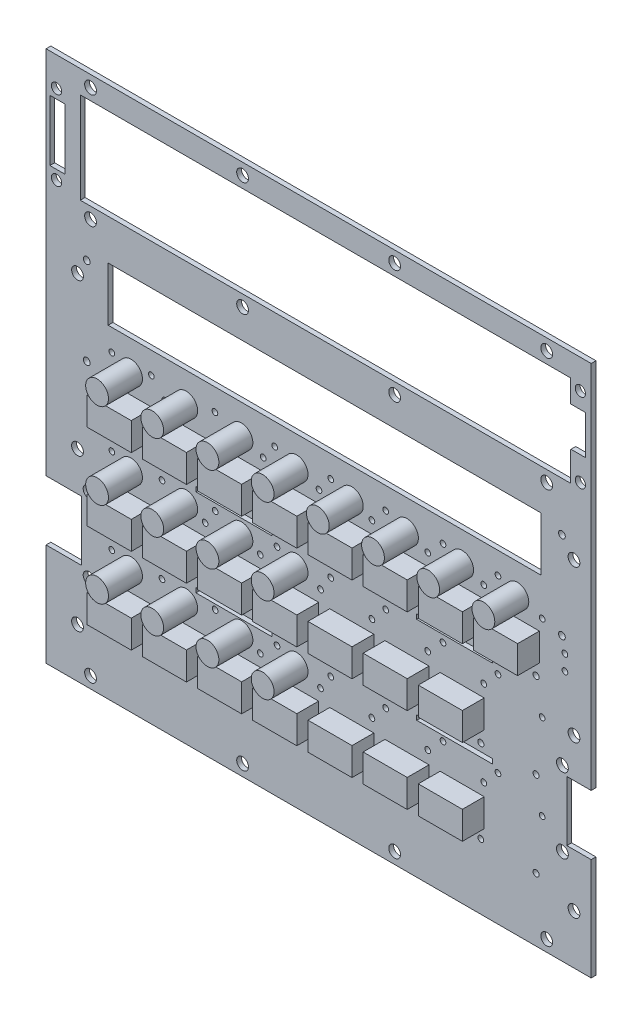
SolidWorks part; units mm, degrees
ref_plane "Front Plane" through (0, 0, 0) normal (0, 0, 1) x (1, 0, 0)
ref_plane "Top Plane" through (0, 0, 0) normal (0, 1, 0) x (1, 0, 0)
ref_plane "Right Plane" through (0, 0, 0) normal (1, 0, 0) x (0, 0, -1)
sketch "Sketch1" plane through (0, 0, 0) normal (0, 0, 1) x (1, 0, 0)
  line L0 (0, 0) -> (182.118, 0)
  line L1 (182.118, 0) -> (182.118, 34.2468)
  line L2 (182.118, 34.2468) -> (173.9875, 34.2468)
  line L3 (173.9875, 34.2468) -> (173.9875, 54.2468)
  line L4 (173.9875, 54.2468) -> (182.118, 54.2468)
  line L5 (182.118, 54.2468) -> (182.118, 177.8)
  line L6 (182.118, 177.8) -> (0, 177.8)
  line L7 (0, 177.8) -> (0, 54.2468)
  line L8 (0, 54.2468) -> (11.8694, 54.2468)
  line L9 (11.8694, 54.2468) -> (11.8694, 34.2468)
  line L10 (11.8694, 34.2468) -> (0, 34.2468)
  line L11 (0, 34.2468) -> (0, 0)
  line L12 (20.7391, 108.1786) -> (20.7391, 126.1796)
  line L13 (20.7391, 126.1796) -> (165.3007, 126.1796)
  line L14 (165.3007, 126.1796) -> (165.3007, 108.1786)
  line L15 (165.3007, 108.1786) -> (20.7391, 108.1786)
  line L16 (1.27, 144.653) -> (1.27, 164.973)
  line L17 (1.27, 164.973) -> (6.35, 164.973)
  line L18 (6.35, 164.973) -> (6.35, 144.653)
  line L19 (6.35, 144.653) -> (1.27, 144.653)
  line L20 (12.7, 170.18) -> (175.26, 170.18)
  line L21 (175.26, 170.18) -> (175.26, 162.6616)
  line L22 (175.26, 162.6616) -> (180.086, 162.6616)
  line L23 (180.086, 162.6616) -> (180.2892, 162.4584)
  line L24 (180.2892, 162.4584) -> (180.2892, 149.606)
  line L25 (180.2892, 149.606) -> (175.3616, 149.606)
  line L26 (175.3616, 149.606) -> (175.26, 149.5044)
  line L27 (175.26, 149.5044) -> (175.26, 139.7)
  line L28 (175.26, 139.7) -> (12.7, 139.7)
  line L29 (12.7, 139.7) -> (11.43, 139.7)
  line L30 (11.43, 139.7) -> (11.43, 170.18)
  line L31 (11.43, 170.18) -> (12.7, 170.18)
  line L32 (50.0634, 45.4152) -> (50.0634, 47.0027)
  line L33 (50.0634, 47.0027) -> (75.4634, 47.0027)
  line L34 (75.4634, 47.0027) -> (75.4634, 45.4152)
  line L35 (75.4634, 45.4152) -> (50.0634, 45.4152)
  line L36 (123.8134, 45.4152) -> (123.8134, 47.0027)
  line L37 (123.8134, 47.0027) -> (149.2134, 47.0027)
  line L38 (149.2134, 47.0027) -> (149.2134, 45.4152)
  line L39 (149.2134, 45.4152) -> (123.8134, 45.4152)
  line L40 (123.8134, 74.6252) -> (123.8134, 76.2127)
  line L41 (123.8134, 76.2127) -> (149.2134, 76.2127)
  line L42 (149.2134, 76.2127) -> (149.2134, 74.6252)
  line L43 (149.2134, 74.6252) -> (123.8134, 74.6252)
  line L44 (50.0634, 74.6252) -> (50.0634, 76.2127)
  line L45 (50.0634, 76.2127) -> (75.4634, 76.2127)
  line L46 (75.4634, 76.2127) -> (75.4634, 74.6252)
  line L47 (75.4634, 74.6252) -> (50.0634, 74.6252)
extrude "BOARD" add sketch "Sketch1" along normal blind 1.5921 separate body
ref_plane "Plane1" through (0, 0, 1.5921) normal (0, 0, 1) x (1, 0, 0)
sketch "Sketch11" plane through (0, 0, 1.5921) normal (0, 0, 1) x (1, 0, 0)
  circle A0 centre (83.7097, 41.1988) radius 3.81
extrude "LED-KINGBRIGHT_3P_2P54-10" add sketch "Sketch11" along normal blind 11.3538 separate body
sketch "Sketch12" plane through (0, 0, 1.5921) normal (0, 0, 1) x (1, 0, 0)
  circle A0 centre (65.2722, 41.1988) radius 3.81
extrude "LED-KINGBRIGHT_3P_2P54-11" add sketch "Sketch12" along normal blind 11.3538 separate body
sketch "Sketch13" plane through (0, 0, 1.5921) normal (0, 0, 1) x (1, 0, 0)
  circle A0 centre (46.8347, 41.1988) radius 3.81
extrude "LED-KINGBRIGHT_3P_2P54-12" add sketch "Sketch13" along normal blind 11.3538 separate body
sketch "Sketch14" plane through (0, 0, 1.5921) normal (0, 0, 1) x (1, 0, 0)
  circle A0 centre (28.3972, 41.1988) radius 3.81
extrude "LED-KINGBRIGHT_3P_2P54-13" add sketch "Sketch14" along normal blind 11.3538 separate body
sketch "Sketch15" plane through (0, 0, 1.5921) normal (0, 0, 1) x (1, 0, 0)
  circle A0 centre (83.7097, 69.7738) radius 3.81
extrude "LED-KINGBRIGHT_3P_2P54-14" add sketch "Sketch15" along normal blind 11.3538 separate body
sketch "Sketch16" plane through (0, 0, 1.5921) normal (0, 0, 1) x (1, 0, 0)
  circle A0 centre (65.2722, 69.7738) radius 3.81
extrude "LED-KINGBRIGHT_3P_2P54-15" add sketch "Sketch16" along normal blind 11.3538 separate body
sketch "Sketch17" plane through (0, 0, 1.5921) normal (0, 0, 1) x (1, 0, 0)
  circle A0 centre (46.8347, 69.7738) radius 3.81
extrude "LED-KINGBRIGHT_3P_2P54-16" add sketch "Sketch17" along normal blind 11.3538 separate body
sketch "Sketch18" plane through (0, 0, 1.5921) normal (0, 0, 1) x (1, 0, 0)
  circle A0 centre (28.3972, 69.7738) radius 3.81
extrude "LED-KINGBRIGHT_3P_2P54-17" add sketch "Sketch18" along normal blind 11.3538 separate body
sketch "Sketch19" plane through (0, 0, 1.5921) normal (0, 0, 1) x (1, 0, 0)
  circle A0 centre (157.4597, 98.3488) radius 3.81
extrude "LED-KINGBRIGHT_3P_2P54-18" add sketch "Sketch19" along normal blind 11.3538 separate body
sketch "Sketch20" plane through (0, 0, 1.5921) normal (0, 0, 1) x (1, 0, 0)
  circle A0 centre (139.0222, 98.3488) radius 3.81
extrude "LED-KINGBRIGHT_3P_2P54-19" add sketch "Sketch20" along normal blind 11.3538 separate body
sketch "Sketch21" plane through (0, 0, 1.5921) normal (0, 0, 1) x (1, 0, 0)
  circle A0 centre (120.5847, 98.3488) radius 3.81
extrude "LED-KINGBRIGHT_3P_2P54-20" add sketch "Sketch21" along normal blind 11.3538 separate body
sketch "Sketch22" plane through (0, 0, 1.5921) normal (0, 0, 1) x (1, 0, 0)
  circle A0 centre (102.1472, 98.3488) radius 3.81
extrude "LED-KINGBRIGHT_3P_2P54-21" add sketch "Sketch22" along normal blind 11.3538 separate body
sketch "Sketch23" plane through (0, 0, 1.5921) normal (0, 0, 1) x (1, 0, 0)
  circle A0 centre (83.7097, 98.3488) radius 3.81
extrude "LED-KINGBRIGHT_3P_2P54-22" add sketch "Sketch23" along normal blind 11.3538 separate body
sketch "Sketch24" plane through (0, 0, 1.5921) normal (0, 0, 1) x (1, 0, 0)
  circle A0 centre (65.2722, 98.3488) radius 3.81
extrude "LED-KINGBRIGHT_3P_2P54-23" add sketch "Sketch24" along normal blind 11.3538 separate body
sketch "Sketch25" plane through (0, 0, 1.5921) normal (0, 0, 1) x (1, 0, 0)
  circle A0 centre (46.8347, 98.3488) radius 3.81
extrude "LED-KINGBRIGHT_3P_2P54-24" add sketch "Sketch25" along normal blind 11.3538 separate body
sketch "Sketch26" plane through (0, 0, 1.5921) normal (0, 0, 1) x (1, 0, 0)
  circle A0 centre (28.3972, 98.3488) radius 3.81
extrude "LED-KINGBRIGHT_3P_2P54-25" add sketch "Sketch26" along normal blind 11.3538 separate body
sketch "Sketch29" plane through (0, 0, 1.5921) normal (0, 0, 1) x (1, 0, 0)
  line L0 (131.6562, 25.3238) -> (131.6562, 34.5948)
  line L1 (131.6562, 34.5948) -> (146.3882, 34.5948)
  line L2 (146.3882, 34.5948) -> (146.3882, 25.3238)
  line L3 (146.3882, 25.3238) -> (131.6562, 25.3238)
extrude "SWITCH-MCDTS2-3" add sketch "Sketch29" along normal blind 7.3 separate body
sketch "Sketch30" plane through (0, 0, 1.5921) normal (0, 0, 1) x (1, 0, 0)
  line L0 (113.2187, 25.3238) -> (113.2187, 34.5948)
  line L1 (113.2187, 34.5948) -> (127.9507, 34.5948)
  line L2 (127.9507, 34.5948) -> (127.9507, 25.3238)
  line L3 (127.9507, 25.3238) -> (113.2187, 25.3238)
extrude "SWITCH-MCDTS2-4" add sketch "Sketch30" along normal blind 7.3 separate body
sketch "Sketch31" plane through (0, 0, 1.5921) normal (0, 0, 1) x (1, 0, 0)
  line L0 (94.7812, 25.3238) -> (94.7812, 34.5948)
  line L1 (94.7812, 34.5948) -> (109.5132, 34.5948)
  line L2 (109.5132, 34.5948) -> (109.5132, 25.3238)
  line L3 (109.5132, 25.3238) -> (94.7812, 25.3238)
extrude "SWITCH-MCDTS2-5" add sketch "Sketch31" along normal blind 7.3 separate body
sketch "Sketch32" plane through (0, 0, 1.5921) normal (0, 0, 1) x (1, 0, 0)
  line L0 (76.3437, 25.3238) -> (76.3437, 34.5948)
  line L1 (76.3437, 34.5948) -> (91.0757, 34.5948)
  line L2 (91.0757, 34.5948) -> (91.0757, 25.3238)
  line L3 (91.0757, 25.3238) -> (76.3437, 25.3238)
extrude "SWITCH-MCDTS2-6" add sketch "Sketch32" along normal blind 7.3 separate body
sketch "Sketch33" plane through (0, 0, 1.5921) normal (0, 0, 1) x (1, 0, 0)
  line L0 (57.9062, 25.3238) -> (57.9062, 34.5948)
  line L1 (57.9062, 34.5948) -> (72.6382, 34.5948)
  line L2 (72.6382, 34.5948) -> (72.6382, 25.3238)
  line L3 (72.6382, 25.3238) -> (57.9062, 25.3238)
extrude "SWITCH-MCDTS2-7" add sketch "Sketch33" along normal blind 7.3 separate body
sketch "Sketch34" plane through (0, 0, 1.5921) normal (0, 0, 1) x (1, 0, 0)
  line L0 (39.4687, 25.3238) -> (39.4687, 34.5948)
  line L1 (39.4687, 34.5948) -> (54.2007, 34.5948)
  line L2 (54.2007, 34.5948) -> (54.2007, 25.3238)
  line L3 (54.2007, 25.3238) -> (39.4687, 25.3238)
extrude "SWITCH-MCDTS2-8" add sketch "Sketch34" along normal blind 7.3 separate body
sketch "Sketch35" plane through (0, 0, 1.5921) normal (0, 0, 1) x (1, 0, 0)
  line L0 (21.0312, 25.3238) -> (21.0312, 34.5948)
  line L1 (21.0312, 34.5948) -> (35.7632, 34.5948)
  line L2 (35.7632, 34.5948) -> (35.7632, 25.3238)
  line L3 (35.7632, 25.3238) -> (21.0312, 25.3238)
extrude "SWITCH-MCDTS2-9" add sketch "Sketch35" along normal blind 7.3 separate body
sketch "Sketch36" plane through (0, 0, 1.5921) normal (0, 0, 1) x (1, 0, 0)
  line L0 (131.6562, 53.8988) -> (131.6562, 63.1698)
  line L1 (131.6562, 63.1698) -> (146.3882, 63.1698)
  line L2 (146.3882, 63.1698) -> (146.3882, 53.8988)
  line L3 (146.3882, 53.8988) -> (131.6562, 53.8988)
extrude "SWITCH-MCDTS2-10" add sketch "Sketch36" along normal blind 7.3 separate body
sketch "Sketch37" plane through (0, 0, 1.5921) normal (0, 0, 1) x (1, 0, 0)
  line L0 (113.2187, 53.8988) -> (113.2187, 63.1698)
  line L1 (113.2187, 63.1698) -> (127.9507, 63.1698)
  line L2 (127.9507, 63.1698) -> (127.9507, 53.8988)
  line L3 (127.9507, 53.8988) -> (113.2187, 53.8988)
extrude "SWITCH-MCDTS2-11" add sketch "Sketch37" along normal blind 7.3 separate body
sketch "Sketch38" plane through (0, 0, 1.5921) normal (0, 0, 1) x (1, 0, 0)
  line L0 (94.7812, 53.8988) -> (94.7812, 63.1698)
  line L1 (94.7812, 63.1698) -> (109.5132, 63.1698)
  line L2 (109.5132, 63.1698) -> (109.5132, 53.8988)
  line L3 (109.5132, 53.8988) -> (94.7812, 53.8988)
extrude "SWITCH-MCDTS2-12" add sketch "Sketch38" along normal blind 7.3 separate body
sketch "Sketch39" plane through (0, 0, 1.5921) normal (0, 0, 1) x (1, 0, 0)
  line L0 (76.3437, 53.8988) -> (76.3437, 63.1698)
  line L1 (76.3437, 63.1698) -> (91.0757, 63.1698)
  line L2 (91.0757, 63.1698) -> (91.0757, 53.8988)
  line L3 (91.0757, 53.8988) -> (76.3437, 53.8988)
extrude "SWITCH-MCDTS2-13" add sketch "Sketch39" along normal blind 7.3 separate body
sketch "Sketch40" plane through (0, 0, 1.5921) normal (0, 0, 1) x (1, 0, 0)
  line L0 (57.9062, 53.8988) -> (57.9062, 63.1698)
  line L1 (57.9062, 63.1698) -> (72.6382, 63.1698)
  line L2 (72.6382, 63.1698) -> (72.6382, 53.8988)
  line L3 (72.6382, 53.8988) -> (57.9062, 53.8988)
extrude "SWITCH-MCDTS2-14" add sketch "Sketch40" along normal blind 7.3 separate body
sketch "Sketch41" plane through (0, 0, 1.5921) normal (0, 0, 1) x (1, 0, 0)
  line L0 (39.4687, 53.8988) -> (39.4687, 63.1698)
  line L1 (39.4687, 63.1698) -> (54.2007, 63.1698)
  line L2 (54.2007, 63.1698) -> (54.2007, 53.8988)
  line L3 (54.2007, 53.8988) -> (39.4687, 53.8988)
extrude "SWITCH-MCDTS2-15" add sketch "Sketch41" along normal blind 7.3 separate body
sketch "Sketch42" plane through (0, 0, 1.5921) normal (0, 0, 1) x (1, 0, 0)
  line L0 (21.0312, 53.8988) -> (21.0312, 63.1698)
  line L1 (21.0312, 63.1698) -> (35.7632, 63.1698)
  line L2 (35.7632, 63.1698) -> (35.7632, 53.8988)
  line L3 (35.7632, 53.8988) -> (21.0312, 53.8988)
extrude "SWITCH-MCDTS2-16" add sketch "Sketch42" along normal blind 7.3 separate body
sketch "Sketch43" plane through (0, 0, 1.5921) normal (0, 0, 1) x (1, 0, 0)
  line L0 (150.0937, 82.4738) -> (150.0937, 91.7448)
  line L1 (150.0937, 91.7448) -> (164.8257, 91.7448)
  line L2 (164.8257, 91.7448) -> (164.8257, 82.4738)
  line L3 (164.8257, 82.4738) -> (150.0937, 82.4738)
extrude "SWITCH-MCDTS2-17" add sketch "Sketch43" along normal blind 7.3 separate body
sketch "Sketch44" plane through (0, 0, 1.5921) normal (0, 0, 1) x (1, 0, 0)
  line L0 (131.6562, 82.4738) -> (131.6562, 91.7448)
  line L1 (131.6562, 91.7448) -> (146.3882, 91.7448)
  line L2 (146.3882, 91.7448) -> (146.3882, 82.4738)
  line L3 (146.3882, 82.4738) -> (131.6562, 82.4738)
extrude "SWITCH-MCDTS2-18" add sketch "Sketch44" along normal blind 7.3 separate body
sketch "Sketch45" plane through (0, 0, 1.5921) normal (0, 0, 1) x (1, 0, 0)
  line L0 (113.2187, 82.4738) -> (113.2187, 91.7448)
  line L1 (113.2187, 91.7448) -> (127.9507, 91.7448)
  line L2 (127.9507, 91.7448) -> (127.9507, 82.4738)
  line L3 (127.9507, 82.4738) -> (113.2187, 82.4738)
extrude "SWITCH-MCDTS2-19" add sketch "Sketch45" along normal blind 7.3 separate body
sketch "Sketch46" plane through (0, 0, 1.5921) normal (0, 0, 1) x (1, 0, 0)
  line L0 (94.7812, 82.4738) -> (94.7812, 91.7448)
  line L1 (94.7812, 91.7448) -> (109.5132, 91.7448)
  line L2 (109.5132, 91.7448) -> (109.5132, 82.4738)
  line L3 (109.5132, 82.4738) -> (94.7812, 82.4738)
extrude "SWITCH-MCDTS2-20" add sketch "Sketch46" along normal blind 7.3 separate body
sketch "Sketch47" plane through (0, 0, 1.5921) normal (0, 0, 1) x (1, 0, 0)
  line L0 (76.3437, 82.4738) -> (76.3437, 91.7448)
  line L1 (76.3437, 91.7448) -> (91.0757, 91.7448)
  line L2 (91.0757, 91.7448) -> (91.0757, 82.4738)
  line L3 (91.0757, 82.4738) -> (76.3437, 82.4738)
extrude "SWITCH-MCDTS2-21" add sketch "Sketch47" along normal blind 7.3 separate body
sketch "Sketch48" plane through (0, 0, 1.5921) normal (0, 0, 1) x (1, 0, 0)
  line L0 (57.9062, 82.4738) -> (57.9062, 91.7448)
  line L1 (57.9062, 91.7448) -> (72.6382, 91.7448)
  line L2 (72.6382, 91.7448) -> (72.6382, 82.4738)
  line L3 (72.6382, 82.4738) -> (57.9062, 82.4738)
extrude "SWITCH-MCDTS2-22" add sketch "Sketch48" along normal blind 7.3 separate body
sketch "Sketch49" plane through (0, 0, 1.5921) normal (0, 0, 1) x (1, 0, 0)
  line L0 (39.4687, 82.4738) -> (39.4687, 91.7448)
  line L1 (39.4687, 91.7448) -> (54.2007, 91.7448)
  line L2 (54.2007, 91.7448) -> (54.2007, 82.4738)
  line L3 (54.2007, 82.4738) -> (39.4687, 82.4738)
extrude "SWITCH-MCDTS2-23" add sketch "Sketch49" along normal blind 7.3 separate body
sketch "Sketch50" plane through (0, 0, 1.5921) normal (0, 0, 1) x (1, 0, 0)
  line L0 (21.0312, 82.4738) -> (21.0312, 91.7448)
  line L1 (21.0312, 91.7448) -> (35.7632, 91.7448)
  line L2 (35.7632, 91.7448) -> (35.7632, 82.4738)
  line L3 (35.7632, 82.4738) -> (21.0312, 82.4738)
extrude "SWITCH-MCDTS2-24" add sketch "Sketch50" along normal blind 7.3 separate body
sketch "Sketch56" plane through (0, 0, 1.5921) normal (0, 0, 1) x (1, 0, 0)
  circle B0 centre (163.703, 21.1074) radius 1.016
  circle B1 centre (163.703, 49.6824) radius 1.016
  circle B2 centre (145.2626, 21.8186) radius 0.9652
  circle B3 centre (126.8476, 21.6154) radius 0.9652
  circle B4 centre (108.4072, 21.7424) radius 0.9652
  circle B5 centre (89.9668, 21.844) radius 0.9652
  circle B6 centre (71.5264, 20.7772) radius 0.9652
  circle B7 centre (53.086, 21.1582) radius 0.9652
  circle B8 centre (34.6472, 21.1328) radius 1.016
  circle B9 centre (145.2626, 49.5554) radius 1.016
  circle B10 centre (126.8222, 49.3522) radius 1.016
  circle B11 centre (108.3818, 49.1236) radius 1.016
  circle B12 centre (89.9414, 49.6824) radius 1.016
  circle B13 centre (71.501, 49.1998) radius 1.016
  circle B14 centre (53.0606, 49.1998) radius 1.016
  circle B15 centre (34.6202, 49.276) radius 1.016
  circle B16 centre (163.703, 78.2574) radius 1.016
  circle B17 centre (145.2626, 77.7748) radius 1.016
  circle B18 centre (126.746, 78.3336) radius 1.016
  circle B19 centre (108.3818, 78.74) radius 1.016
  circle B20 centre (89.9414, 78.3336) radius 1.016
  circle B21 centre (71.501, 78.2574) radius 1.016
  circle B22 centre (53.0606, 78.4098) radius 1.016
  circle B23 centre (34.6202, 78.0542) radius 1.016
  circle B24 centre (91.694, 38.6588) radius 0.9525
  circle B25 centre (77.1652, 43.7388) radius 0.9525
  circle B26 centre (71.5772, 38.6588) radius 0.9525
  circle B27 centre (56.4896, 43.7388) radius 0.9525
  circle B28 centre (38.735, 43.7388) radius 0.9525
  circle B29 centre (21.8948, 38.6588) radius 0.9525
  circle B30 centre (21.971, 43.7388) radius 0.9525
  circle B31 centre (77.1652, 72.3138) radius 0.9525
  circle B32 centre (91.694, 67.2338) radius 0.9525
  circle B33 centre (71.5772, 67.2338) radius 0.9525
  circle B34 centre (56.4896, 72.3138) radius 0.9525
  circle B35 centre (53.1368, 67.2338) radius 0.9525
  circle B36 centre (38.735, 72.3138) radius 0.9525
  circle B37 centre (21.8948, 67.2338) radius 0.9525
  circle B38 centre (21.971, 72.3138) radius 0.9525
  circle B39 centre (165.735, 95.8088) radius 0.9525
  circle B40 centre (150.9776, 100.8888) radius 0.9525
  circle B41 centre (146.2278, 95.8088) radius 0.9525
  circle B42 centre (132.6134, 100.8888) radius 0.9525
  circle B43 centre (113.4872, 100.8888) radius 0.9525
  circle B44 centre (127.508, 95.8088) radius 0.9525
  circle B45 centre (108.8644, 95.8088) radius 0.9525
  circle B46 centre (95.0976, 100.8888) radius 0.9525
  circle B47 centre (91.186, 95.8088) radius 0.9525
  circle B48 centre (76.3778, 100.8888) radius 0.9525
  circle B49 centre (72.5424, 95.8088) radius 0.9525
  circle B50 centre (56.4134, 100.8888) radius 0.9525
  circle B51 centre (39.7256, 95.8088) radius 0.9525
  circle B52 centre (35.179, 100.8888) radius 0.9525
  circle B53 centre (24.2062, 95.8088) radius 0.9525
  circle B54 centre (21.971, 100.8888) radius 0.9525
  circle B55 centre (132.6134, 72.3138) radius 0.9525
  circle B56 centre (146.2278, 67.2338) radius 0.9525
  circle B57 centre (113.4872, 72.3138) radius 0.9525
  circle B58 centre (127.508, 67.2338) radius 0.9525
  circle B59 centre (95.0976, 72.3138) radius 0.9525
  circle B60 centre (108.8644, 67.2338) radius 0.9525
  circle B61 centre (150.9776, 43.7388) radius 0.9525
  circle B62 centre (132.6134, 43.7388) radius 0.9525
  circle B63 centre (113.4872, 43.7388) radius 0.9525
  circle B64 centre (95.0976, 43.7388) radius 0.9525
  circle B65 centre (108.8644, 38.6588) radius 0.9525
  circle B66 centre (150.9776, 72.3138) radius 0.9525
  circle B67 centre (165.735, 67.2338) radius 0.9525
  circle B68 centre (173.3296, 89.4588) radius 0.9525
  circle B69 centre (173.355, 84.3534) radius 0.9525
  circle B70 centre (176.3725, 118.11) radius 1.9685
  circle B71 centre (176.3725, 67.31) radius 1.9685
  circle B72 centre (176.3725, 16.51) radius 1.9685
  circle B73 centre (167.259, 135.89) radius 1.9685
  circle B74 centre (116.459, 135.89) radius 1.9685
  circle B75 centre (65.659, 135.89) radius 1.9685
  circle B76 centre (14.859, 135.89) radius 1.9685
  circle B77 centre (10.5105, 118.11) radius 1.9685
  circle B78 centre (10.5105, 67.31) radius 1.9685
  circle B79 centre (10.5105, 16.51) radius 1.9685
  circle B80 centre (165.735, 38.6588) radius 0.9525
  circle B81 centre (146.2278, 38.6588) radius 0.9525
  circle B82 centre (127.508, 38.6588) radius 0.9525
  circle B83 centre (14.859, 173.99) radius 1.9685
  circle B84 centre (65.659, 173.99) radius 1.9685
  circle B85 centre (116.459, 173.99) radius 1.9685
  circle B86 centre (167.259, 173.99) radius 1.9685
  circle B87 centre (167.259, 3.81) radius 1.9685
  circle B88 centre (116.459, 3.81) radius 1.9685
  circle B89 centre (65.659, 3.81) radius 1.9685
  circle B90 centre (14.859, 3.81) radius 1.9685
  circle B91 centre (172.5066, 56.7436) radius 1.9685
  circle B92 centre (172.5066, 31.75) radius 1.9685
  circle B93 centre (14.3688, 56.7436) radius 1.9685
  circle B94 centre (14.3688, 31.75) radius 1.9685
  circle B95 centre (172.3415, 123.3754) radius 1.1303
  circle B96 centre (172.3415, 94.1654) radius 1.1303
  circle B97 centre (13.5915, 94.1654) radius 1.1303
  circle B98 centre (13.5915, 123.3754) radius 1.1303
  circle B99 centre (178.5137, 141.5618) radius 1.7145
  circle B100 centre (178.5137, 168.0616) radius 1.7145
  circle B101 centre (3.5001, 168.0616) radius 1.7145
  circle B102 centre (3.5001, 141.5618) radius 1.7145
sketch_block_instance "Block-Model-1"
sketch_block "Block-Model"
extrude "Cut-Extrude1" cut sketch "Sketch56" against normal blind 10
